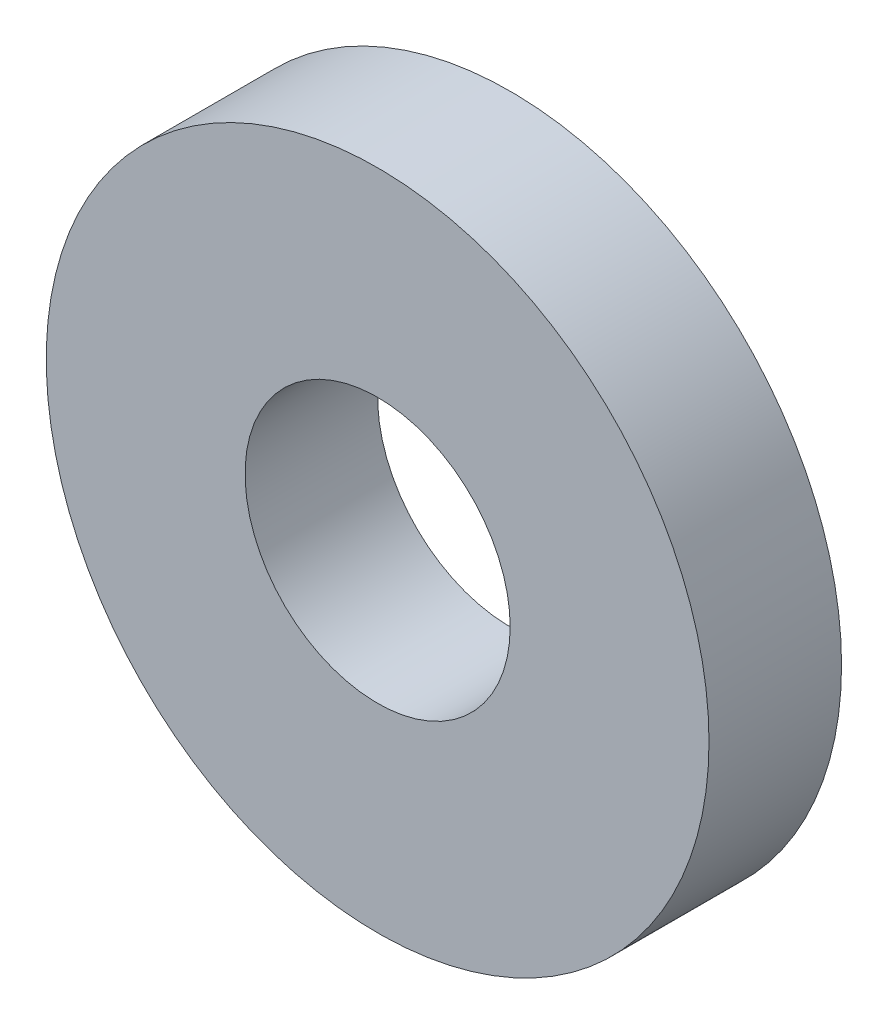
SolidWorks part; units mm, degrees
ref_plane "Front Plane" through (0, 0, 0) normal (0, 0, 1) x (1, 0, 0)
ref_plane "Top Plane" through (0, 0, 0) normal (0, 1, 0) x (1, 0, 0)
ref_plane "Right Plane" through (0, 0, 0) normal (1, 0, 0) x (0, 0, -1)
sketch "Sketch5" plane through (0, 0, 0) normal (0, 0, 1) x (1, 0, 0)
  circle A0 centre (0, 0) radius 25
  circle A1 centre (0, 0) radius 10
  dimension "D1" = 50
  dimension "D2" = 20
extrude "Boss-Extrude1" add sketch "Sketch5" along normal blind 10
